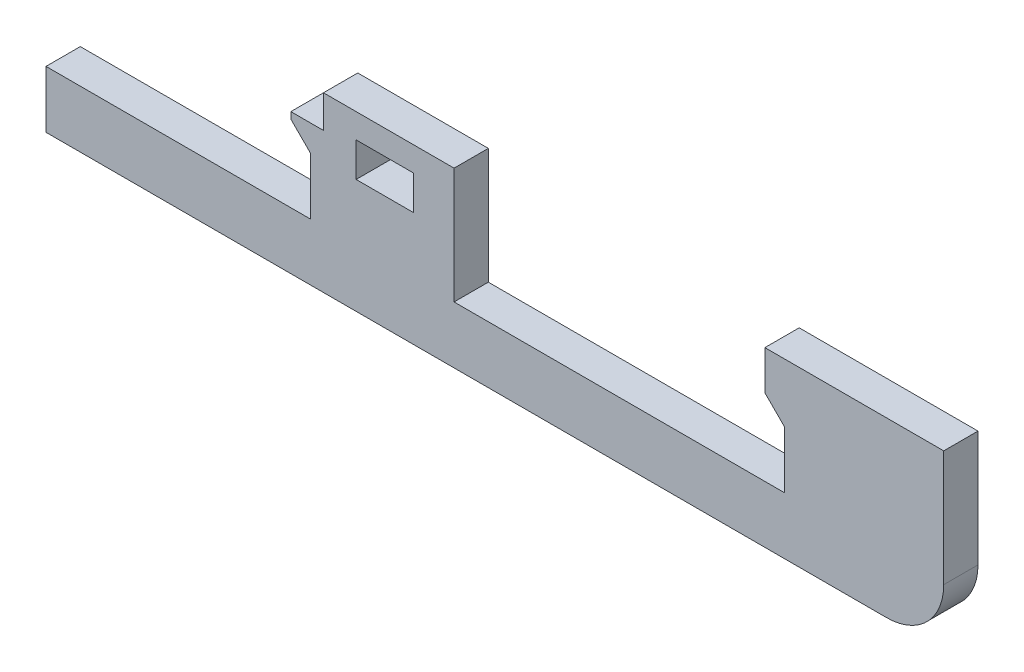
SolidWorks part; units mm, degrees
ref_plane "Front Plane" through (0, 0, 0) normal (0, 0, 1) x (1, 0, 0)
ref_plane "Top Plane" through (0, 0, 0) normal (0, 1, 0) x (1, 0, 0)
ref_plane "Right Plane" through (0, 0, 0) normal (1, 0, 0) x (0, 0, -1)
sketch "Sketch1" plane through (0, 0, 0) normal (0, 0, 1) x (1, 0, 0)
  line L1 (-37.7297, 18.8387) -> (101.9703, 18.8387)
  line L2 (-37.7297, 18.8387) -> (-37.7297, -8.0853)
  line L3 (-37.7297, -8.0853) -> (101.9703, -8.0853)
  line L4 (101.9703, 18.8387) -> (101.9703, -8.0853)
  dimension "D1" = 26.924
  dimension "D2" = 139.7
extrude "Boss-Extrude1" add sketch "Sketch1" along normal blind 5.334
sketch "Sketch2" plane through (0, 0, 5.334) normal (0, 0, 1) x (1, 0, 0)
  line L0 (-37.7297, -8.0853) -> (101.9703, -8.0853) construction
  line L1 (-37.7297, 18.8387) -> (0.3703, 18.8387)
  line L2 (-37.7297, 18.8387) -> (-37.7297, 0.8047)
  line L3 (-37.7297, 0.8047) -> (0.3703, 0.8047)
  line L4 (0.3703, 18.8387) -> (0.3703, 0.8047)
  dimension "D1" = 38.1
  dimension "D2" = 8.89
extrude "Cut-Extrude1" cut sketch "Sketch2" against normal through all
sketch "Sketch3" plane through (0, 0, 5.334) normal (0, 0, 1) x (1, 0, 0)
  line L0 (101.9703, 18.8387) -> (0.3703, 18.8387) construction
  line L1 (25.7703, 18.8387) -> (74.1421, 18.8387)
  line L2 (25.7703, 18.8387) -> (25.7703, 0.8047)
  line L3 (25.7703, 0.8047) -> (74.1421, 0.8047)
  line L4 (74.1421, 18.8387) -> (74.1421, 0.8047)
  line L5 (0.3703, 0.8047) -> (0.3703, 18.8387) construction
  line L6 (-37.7297, 0.8047) -> (0.3703, 0.8047) construction
  dimension "D1" = 25.4
  dimension "D2" = 48.3718
  dimension "D3" = 0
extrude "Cut-Extrude3" cut sketch "Sketch3" against normal through all
sketch "Sketch4" plane through (0, 0, 5.334) normal (0, 0, 1) x (1, 0, 0)
  line L1 (0.3703, 18.8387) -> (5.4503, 18.8387)
  line L2 (0.3703, 18.8387) -> (0.3703, 13.7587)
  line L3 (0.3703, 13.7587) -> (5.4503, 13.7587)
  line L4 (5.4503, 18.8387) -> (5.4503, 13.7587)
  dimension "D1" = 5.08
  dimension "D2" = 5.08
extrude "Cut-Extrude4" cut sketch "Sketch4" against normal through all
fillet "Fillet1" radius 8.89 1 edges at (101.9703, -8.0853, 2.667)
sketch "Sketch5" plane through (0, 0, 5.334) normal (0, 0, 1) x (1, 0, 0)
  line L0 (0.3703, 9.6947) -> (25.7703, 9.6947) construction
  line L1 (19.4203, 9.6947) -> (10.5303, 9.6947)
  line L2 (19.4203, 9.6947) -> (19.4203, 15.0287)
  line L3 (19.4203, 15.0287) -> (10.5303, 15.0287)
  line L4 (10.5303, 9.6947) -> (10.5303, 15.0287)
  line L5 (25.7703, 18.8387) -> (25.7703, 0.8047) construction
  dimension "D1" = 5.334
  dimension "D2" = 8.89
  dimension "D3" = 6.35
extrude "Cut-Extrude5" cut sketch "Sketch5" against normal through all
sketch "Sketch6" plane through (0, 0, 5.334) normal (0, 0, 1) x (1, 0, 0)
  line L0 (101.9703, 18.8387) -> (74.1421, 18.8387) construction
  line L1 (74.1421, 0.8047) -> (77.1901, 0.8047)
  line L2 (74.1421, 0.8047) -> (74.1421, 9.6947)
  line L3 (74.1421, 9.6947) -> (77.1901, 9.6947)
  line L4 (77.1901, 0.8047) -> (77.1901, 9.6947)
  dimension "D1" = 9.144
  dimension "D2" = 3.048
extrude "Cut-Extrude6" cut sketch "Sketch6" against normal through all
sketch "Sketch7" plane through (0, 0, 5.334) normal (0, 0, 1) x (1, 0, 0)
  line L0 (77.1901, 9.6947) -> (74.1421, 12.7427)
  line L1 (74.1421, 9.6947) -> (74.1421, 18.8387) construction
  line L2 (74.1421, 12.7427) -> (74.1421, 9.6947)
  line L3 (74.1421, 9.6947) -> (77.1901, 9.6947)
extrude "Cut-Extrude7" cut sketch "Sketch7" against normal through all
sketch "Sketch8" plane through (0, 0, 5.334) normal (0, 0, 1) x (1, 0, 0)
  line L0 (0.3703, 1.3127) -> (3.4183, 4.3607)
  line L1 (0.3703, 0.8047) -> (0.3703, 13.7587) construction
  line L2 (0.3703, 4.3607) -> (25.7703, 4.3607) construction
  line L3 (3.4183, 4.3607) -> (3.4183, 9.6947)
  line L4 (0.3703, 9.6947) -> (25.7703, 9.6947) construction
  line L5 (3.4183, 9.6947) -> (0.3703, 12.7427)
  line L6 (0.3703, 12.7427) -> (0.3703, 1.3127)
  dimension "D1" = 3.048
  dimension "D2" = 3.048
extrude "Cut-Extrude8" cut sketch "Sketch8" against normal through all
sketch "Sketch9" plane through (0, 0, 5.334) normal (0, 0, 1) x (1, 0, 0)
  line L0 (3.4183, 4.3607) -> (3.4183, 0.8047)
  line L1 (0.3703, 0.8047) -> (3.4183, 0.8047)
extrude "Cut-Extrude9" cut sketch "Sketch9" against normal through all and the other way through all
equation "\"MDF\"= .21in"
equation "\"Foamcore\"= .13in"
equation "\"Gmaterial\"= \"MDF\""
equation "\"D1@Boss-Extrude1\"=\"MDF\""
equation "\"D1@Sketch5\"=\"MDF\""
